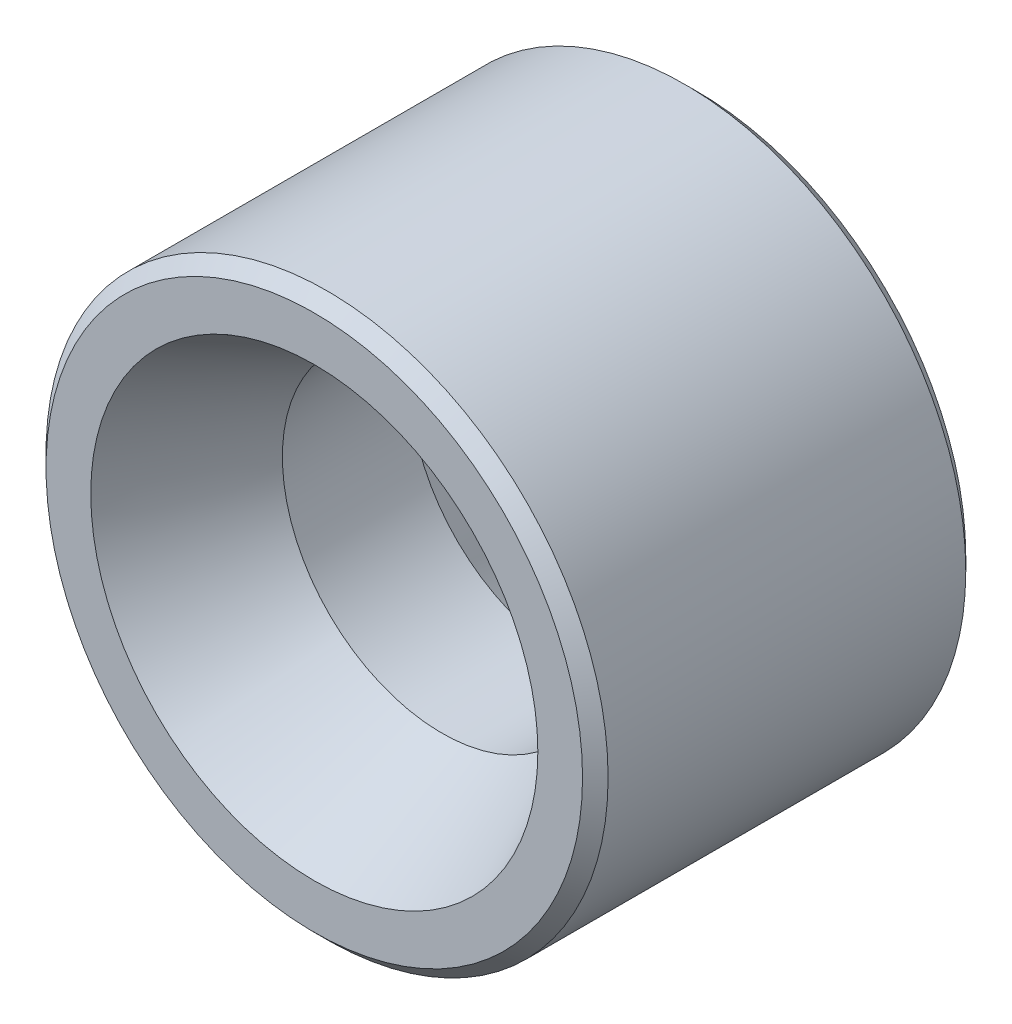
SolidWorks part; units mm, degrees
material "PE High Density"
ref_plane "Front Plane" through (0, 0, 0) normal (0, 0, 1) x (1, 0, 0)
ref_plane "Top Plane" through (0, 0, 0) normal (0, 1, 0) x (1, 0, 0)
ref_plane "Right Plane" through (0, 0, 0) normal (1, 0, 0) x (0, 0, -1)
sketch "Sketch1" plane through (0, 0, 0) normal (0, 0, 1) x (1, 0, 0)
  circle A0 centre (0, 0) radius 12.5
  circle A1 centre (0, 0) radius 22
  dimension "D1" = 25
  dimension "D2" = 44
extrude "Boss-Extrude1" add sketch "Sketch1" along normal mid plane 30
chamfer "Chamfer1" distance 1 angle 45 2 edges at (22, 0, -15) (22, 0, 15)
chamfer "Chamfer2" distance 5 distance2 10 1 edges at (12.5, 0, 15)
chamfer "Chamfer3" distance 10 distance2 5 1 edges at (12.5, 0, -15)
revolve "Cut-Revolve1" cut sketch "Sketch2" angle 360 about L0
sketch "Sketch2" plane through (-103.1364, -329.9949, 0) normal (0, 0, 1) x (-1, 0, 0)
  line L0 (-96.4969, -304.9949) -> (-96.4969, -316.4949)
  line L1 (-96.4969, -316.4949) -> (-103.1364, -304.9949)
  line L3 (-103.1364, -304.9949) -> (-96.4969, -304.9949)
mirror "Mirror6" [suppressed] about plane through (0, 0, 0) normal (0, 1, 0)
